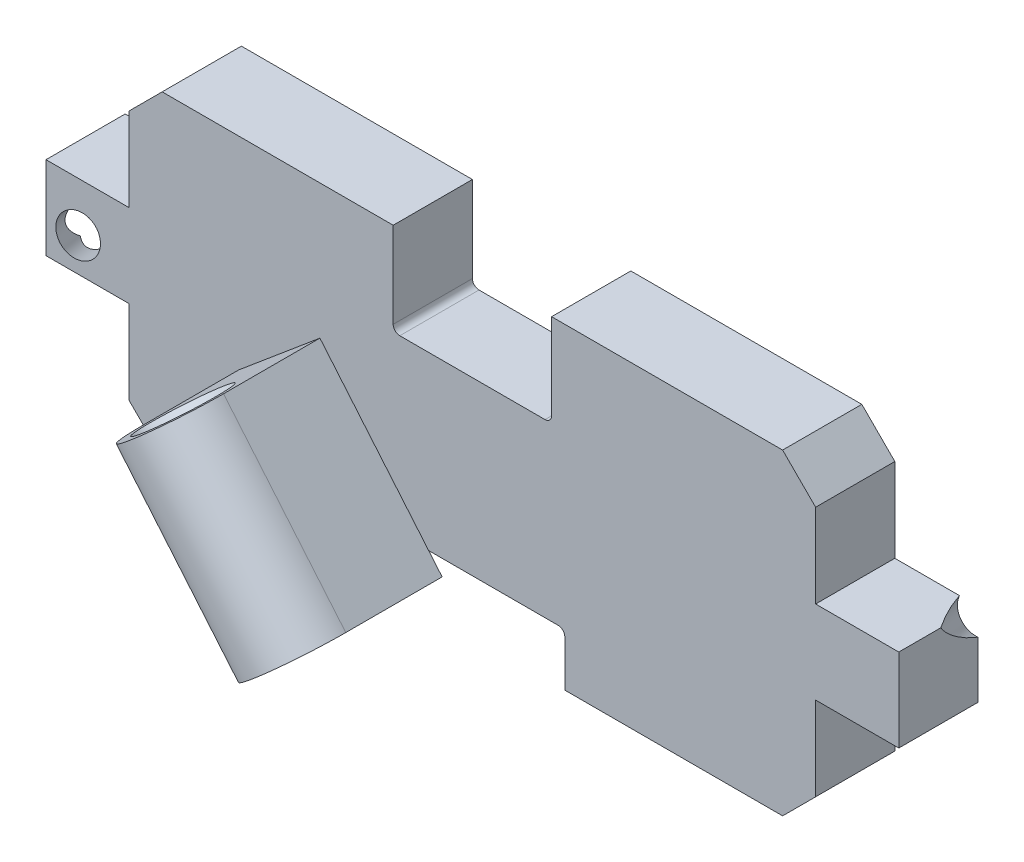
SolidWorks part; units mm, degrees
ref_plane "Front Plane" through (0, 0, 0) normal (0, 0, 1) x (1, 0, 0)
ref_plane "Top Plane" through (0, 0, 0) normal (0, 1, 0) x (1, 0, 0)
ref_plane "Right Plane" through (0, 0, 0) normal (1, 0, 0) x (0, 0, -1)
sketch "Sketch1" plane through (0, 0, 0) normal (0, 0, 1) x (1, 0, 0)
  line L16 (-23.5, -12) -> (-7, -12)
  line L17 (-7, -12) -> (-7, -8.5)
  line L18 (-6.5, -8) -> (6.5, -8)
  line L19 (7, -8.5) -> (7, -12)
  line L20 (7, -12) -> (23.5, -12)
  line L21 (23.5, -12) -> (26, -9.5)
  line L22 (26, -9.5) -> (26, -3.15)
  line L23 (26, 9.5) -> (23.5, 12)
  line L24 (23.5, 12) -> (6, 12)
  line L25 (6, 12) -> (6, 5.5)
  line L26 (5.5, 5) -> (-5.5, 5)
  line L27 (-6, 5.5) -> (-6, 12)
  line L28 (-6, 12) -> (-23.5, 12)
  line L29 (-23.5, 12) -> (-26, 9.5)
  line L30 (-26, 9.5) -> (-26, 3.15)
  line L31 (-26, -9.5) -> (-23.5, -12)
  line L32 (-23.5, -12) -> (-7, -12)
  line L33 (-7, -12) -> (-7, -8.5)
  line L34 (-6.5, -8) -> (6.5, -8)
  line L35 (7, -8.5) -> (7, -12)
  line L36 (7, -12) -> (23.5, -12)
  line L37 (23.5, -12) -> (26, -9.5)
  line L38 (26, -9.5) -> (26, -3.15)
  line L39 (26, 9.5) -> (23.5, 12)
  line L40 (23.5, 12) -> (6, 12)
  line L41 (6, 12) -> (6, 5.5)
  line L42 (5.5, 5) -> (-5.5, 5)
  line L43 (-6, 5.5) -> (-6, 12)
  line L44 (-6, 12) -> (-23.5, 12)
  line L45 (-23.5, 12) -> (-26, 9.5)
  line L46 (-26, 9.5) -> (-26, 3.15)
  line L47 (-26, -9.5) -> (-23.5, -12)
  line L224 (26, -3.15) -> (32.3, -3.15)
  line L225 (26, -3.15) -> (32.3, -3.15)
  line L226 (32.3, -3.15) -> (32.3, 3.15)
  line L227 (32.3, -3.15) -> (32.3, 3.15)
  line L228 (32.3, 3.15) -> (26, 3.15)
  line L229 (32.3, 3.15) -> (26, 3.15)
  line L230 (26, 3.15) -> (26, 9.5)
  line L231 (26, 3.15) -> (26, 9.5)
  line L232 (-26, 3.15) -> (-32.3, 3.15)
  line L233 (-26, 3.15) -> (-32.3, 3.15)
  line L234 (-32.3, 3.15) -> (-32.3, -3.15)
  line L235 (-32.3, 3.15) -> (-32.3, -3.15)
  line L236 (-32.3, -3.15) -> (-26, -3.15)
  line L237 (-32.3, -3.15) -> (-26, -3.15)
  line L238 (-26, -3.15) -> (-26, -9.5)
  line L239 (-26, -3.15) -> (-26, -9.5)
  arc A4 (-6.5, -8) -> (-7, -8.5) centre (-6.5, -8.5) ccw
  arc A5 (7, -8.5) -> (6.5, -8) centre (6.5, -8.5) ccw
  arc A6 (5.5, 5) -> (6, 5.5) centre (5.5, 5.5) ccw
  arc A7 (-6, 5.5) -> (-5.5, 5) centre (-5.5, 5.5) ccw
  arc A8 (-6.5, -8) -> (-7, -8.5) centre (-6.5, -8.5) ccw
  arc A9 (7, -8.5) -> (6.5, -8) centre (6.5, -8.5) ccw
  arc A10 (5.5, 5) -> (6, 5.5) centre (5.5, 5.5) ccw
  arc A11 (-6, 5.5) -> (-5.5, 5) centre (-5.5, 5.5) ccw
  dimension "D1" = 0
extrude "Boss-Extrude1" add sketch "Sketch1" along normal blind 6 from offset 5
chamfer "Chamfer1" distance 4.5 5 edges at (-7, -10.25, 5) (7, -10.25, 5) (-6.8536, -8.1464, 5) (6.8536, -8.1464, 5) (0, -8, 5)
sketch "Sketch2" plane through (26, 0, 0) normal (1, 0, 0) x (0, 0, -1)
  line L0 (-11, -9.5) -> (-11, -3.15) construction
  line L1 (-11, 3.15) -> (-5, 3.15)
  line L2 (-11, 3.15) -> (-11, -3.15)
  line L3 (-11, -3.15) -> (-5, -3.15)
  line L4 (-5, 3.15) -> (-5, -3.15)
  line L5 (-5, -9.5) -> (-5, -3.15) construction
  point P8 (-5, 0)
  dimension "D1" = 6.3
extrude "Boss-Extrude2" add sketch "Sketch2" along normal blind 6.3
mirror "Mirror1" about plane through (0, 0, 0) normal (1, 0, 0) of "Boss-Extrude2"
sketch "Sketch3" plane through (0, 0, 11) normal (0, 0, 1) x (1, 0, 0)
  line L0 (11.5514, 1.8168) -> (2.2919, -9.2183)
  line L1 (2.2919, -9.2183) -> (8.4391, -14.3764)
  line L2 (8.4391, -14.3764) -> (17.6986, -3.3413)
  line L4 (26, 9.5) -> (23.5, 12)
  line L5 (11.5514, 1.8168) -> (17.6986, -3.3413)
  line L6 (7, -12) -> (23.5, -12) construction
  line L7 (0, 7.2308) -> (0, -15.9549)
  line L8 (-11.5514, 1.8168) -> (-2.2919, -9.2183)
  line L9 (-11.5514, 1.8168) -> (-17.6986, -3.3413)
  line L10 (-8.4391, -14.3764) -> (-17.6986, -3.3413)
  line L11 (-2.2919, -9.2183) -> (-8.4391, -14.3764)
  dimension "D1" = 30
  dimension "D2" = 50
extrude "Boss-Extrude3" add sketch "Sketch3" along normal blind 7.3 contours L1 L2 L5 L0
sketch "Sketch4" plane through (5.6674, 6.7541, 0) normal (0.6428, 0.766, 0) x (0.766, -0.6428, 0)
  line L0 (7.6811, -18.3) -> (15.7056, -18.3) construction
  line L1 (15.7056, -18.3) -> (7.6811, -18.3)
  arc A0 (15.7056, -18.3) -> (7.6811, -18.3) centre (11.6933, -18.3) cw
extrude "Boss-Extrude4" add sketch "Sketch4" against normal up to vertex
hole_wizard "CSK for M3 SFHCS1" positions "Sketch5" profile "Sketch6" countersink size "M3" standard "ANSI Metric" end condition through all
sketch "Sketch5" plane through (5.6674, 6.7541, 0) normal (0.6428, 0.766, 0) x (0.766, -0.6428, 0)
  point P0 (11.6933, -18.3)
sketch "Sketch6" plane through (14.625, -0.7622, 18.3) normal (0, 0, 1) x (-0.766, 0.6428, 0)
  line L0 (0, 0) -> (0, 40.5919)
  line L1 (0, 40.5919) -> (1.5, 40.5919)
  line L2 (1.5, 40.5919) -> (1.5, 1.65)
  line L3 (1.5, 1.65) -> (3.15, 0)
  line L5 (3.15, 0) -> (0, 0)
  line L6 (-1.5, 1.65) -> (-3.15, 0) construction
  line L11 (0, -6.35) -> (0, 107.95) construction
  dimension "Thru Hole Dia." = 3
  dimension "Thru Hole Depth" = 40.5919
  dimension "Near C'Sink Dia." = 6.3
  dimension "Near C'Sink Angle" = 90
mirror "Mirror11" about plane through (0, 0, 0) normal (1, 0, 0) of "Boss-Extrude3"
sketch "Sketch7" plane through (-5.6674, 6.7541, 0) normal (-0.6428, 0.766, 0) x (0.766, 0.6428, 0)
  line L0 (-7.6811, -18.3) -> (-15.7056, -18.3) construction
  line L1 (-7.6811, -18.3) -> (-7.6811, -11) construction
  line L2 (-15.7056, -18.3) -> (-7.6811, -18.3)
  arc A0 (-15.7056, -18.3) -> (-7.6811, -18.3) centre (-11.6933, -18.3) ccw
extrude "Boss-Extrude5" add sketch "Sketch7" against normal up to vertex
hole_wizard "CSK for M3 SFHCS2" positions "Sketch8" profile "Sketch9" countersink size "M3" standard "ANSI Metric" end condition through all
sketch "Sketch8" plane through (-5.6674, 6.7541, 0) normal (-0.6428, 0.766, 0) x (0.766, 0.6428, 0)
  point P0 (-11.6933, -18.3)
sketch "Sketch9" plane through (-14.625, -0.7622, 18.3) normal (0, 0, 1) x (-0.766, -0.6428, 0)
  line L0 (0, 0) -> (0, 40.5919)
  line L1 (0, 40.5919) -> (1.5, 40.5919)
  line L2 (1.5, 40.5919) -> (1.5, 1.65)
  line L3 (1.5, 1.65) -> (3.15, 0)
  line L5 (3.15, 0) -> (0, 0)
  line L6 (-1.5, 1.65) -> (-3.15, 0) construction
  line L11 (0, -6.35) -> (0, 107.95) construction
  dimension "Thru Hole Dia." = 3
  dimension "Thru Hole Depth" = 40.5919
  dimension "Near C'Sink Dia." = 6.3
  dimension "Near C'Sink Angle" = 90
sketch "Sketch10" plane through (0, 0, 11) normal (0, 0, 1) x (1, 0, 0)
  line L1 (0, -15.6208) -> (19.4439, -15.6208)
  line L2 (0, -15.6208) -> (0, 3.8231)
  line L3 (0, 3.8231) -> (19.4439, 3.8231)
  line L4 (19.4439, -15.6208) -> (19.4439, 3.8231)
extrude "Cut-Extrude1" cut sketch "Sketch10" along normal blind 15
hole_wizard "CSK for M3 SFHCS3" positions "Sketch11" profile "Sketch12" countersink size "M3" standard "ANSI Metric"
sketch "Sketch11" plane through (1373.8349, -105.6168, -567.7831) normal (0.4295, 0.3604, 0.828) x (0.6343, 0.5322, -0.5607)
  line L0 (-1161.4085, 984.7533) -> (-1111.922, 943.2292)
  line L6 (-1156.9707, 985.1415) -> (-1161.0202, 980.3154)
  line L11 (-1112.3103, 947.667) -> (-1116.3598, 942.8409)
  point P2 (-1114.3351, 945.254)
  point P48 (-1158.9954, 982.7285)
sketch "Sketch12" plane through (59.4044, 25.3865, 57.0036) normal (0.5862, 0.5862, -0.5592) x (0.6869, -0.7256, -0.0405)
  line L0 (0, 0) -> (0, 96.7788)
  line L1 (0, 96.7788) -> (1.5, 96.7788)
  line L2 (1.5, 96.7788) -> (1.5, 1.65)
  line L3 (1.5, 1.65) -> (3.15, 0)
  line L4 (3.15, 0) -> (0, 0)
  line L5 (-1.5, 1.65) -> (-3.15, 0) construction
  line L6 (0, -6.35) -> (0, 107.95) construction
  dimension "Thru Hole Dia." = 3
  dimension "Thru Hole Depth" = 96.7788
  dimension "Near C'Sink Dia." = 6.3
  dimension "Near C'Sink Angle" = 90
